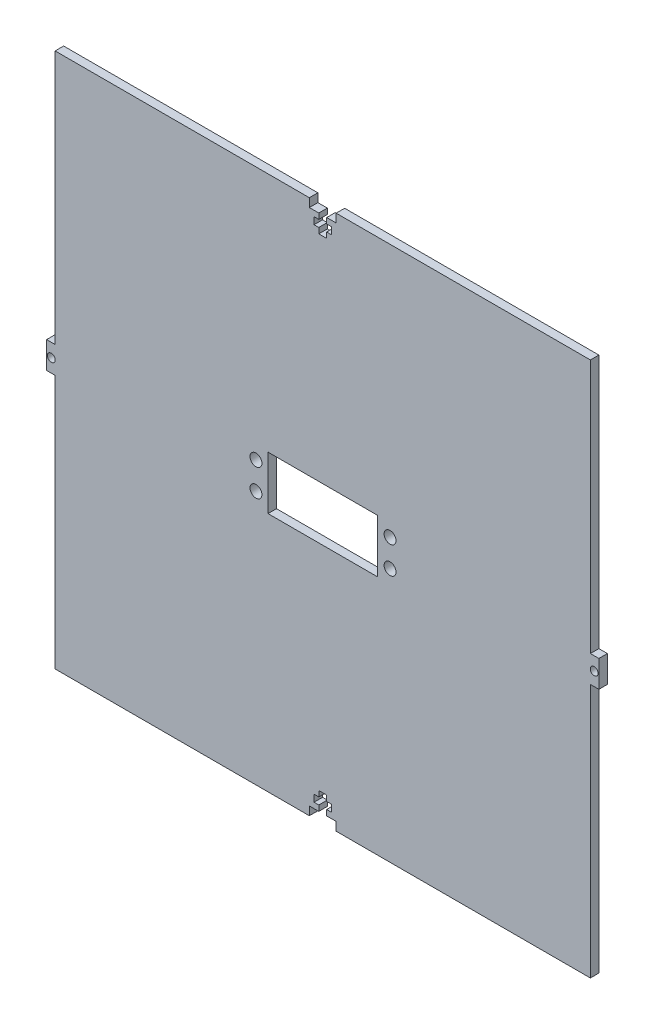
SolidWorks part; units mm, degrees
ref_plane "Front Plane" through (0, 0, 0) normal (0, 0, 1) x (1, 0, 0)
ref_plane "Top Plane" through (0, 0, 0) normal (0, 1, 0) x (1, 0, 0)
ref_plane "Right Plane" through (0, 0, 0) normal (1, 0, 0) x (0, 0, -1)
sketch "Sketch2" plane through (0, 0, 0) normal (0, 0, 1) x (1, 0, 0)
  line L1 (-100, -100) -> (100, -100)
  line L2 (-100, -100) -> (-100, 100)
  line L3 (-100, 100) -> (100, 100)
  line L4 (100, -100) -> (100, 100)
  line L5 (-100, -100) -> (100, 100) construction
  line L6 (-100, 100) -> (100, -100) construction
  point P0 (0, 0)
  dimension "D1" = 200
  dimension "D2" = 200
extrude "Boss-Extrude1" add sketch "Sketch2" along normal blind 3.18
sketch "Sketch3" plane through (0, 0, 3.18) normal (0, 0, 1) x (1, 0, 0)
  line L0 (100, 100) -> (-100, 100) construction
  line L1 (-5, 100) -> (5, 100)
  line L2 (-5, 100) -> (-5, 96.82)
  line L3 (-5, 96.82) -> (-1.47, 96.82)
  line L4 (5, 100) -> (5, 96.82)
  line L5 (0, 100) -> (0, 25.4128) construction
  line L6 (1.47, 92.14) -> (3.25, 92.14)
  line L8 (-1.47, 96.82) -> (-1.47, 94.74)
  line L9 (-1.47, 90.07) -> (1.47, 90.07)
  line L10 (1.47, 96.82) -> (1.47, 94.74)
  line L11 (-3.25, 94.74) -> (-1.47, 94.74)
  line L12 (-3.25, 94.74) -> (-3.25, 92.14)
  line L13 (-3.25, 92.14) -> (-1.47, 92.14)
  line L14 (3.25, 94.74) -> (3.25, 92.14)
  line L15 (-1.47, 92.14) -> (-1.47, 90.07)
  line L16 (1.47, 94.74) -> (3.25, 94.74)
  line L17 (1.47, 96.82) -> (5, 96.82)
  line L18 (1.47, 92.14) -> (1.47, 90.07)
  line L19 (-100, 0) -> (100, 0) construction
  line L20 (-100, 100) -> (-100, -100) construction
  line L21 (100, -100) -> (100, 100) construction
  line L22 (1.47, -96.82) -> (5, -96.82)
  line L23 (5, -100) -> (5, -96.82)
  line L24 (-5, -100) -> (5, -100)
  line L25 (-5, -100) -> (-5, -96.82)
  line L26 (-5, -96.82) -> (-1.47, -96.82)
  line L27 (-1.47, -96.82) -> (-1.47, -94.74)
  line L28 (-3.25, -94.74) -> (-1.47, -94.74)
  line L29 (-3.25, -94.74) -> (-3.25, -92.14)
  line L30 (-3.25, -92.14) -> (-1.47, -92.14)
  line L31 (-1.47, -92.14) -> (-1.47, -90.07)
  line L32 (-1.47, -90.07) -> (1.47, -90.07)
  line L33 (1.47, -92.14) -> (1.47, -90.07)
  line L34 (1.47, -92.14) -> (3.25, -92.14)
  line L35 (3.25, -94.74) -> (3.25, -92.14)
  line L36 (1.47, -94.74) -> (3.25, -94.74)
  line L37 (1.47, -96.82) -> (1.47, -94.74)
  dimension "D1" = 3.18
  dimension "D2" = 10
  dimension "D3" = 2.94
  dimension "D4" = 2.6
  dimension "D5" = 6.75
  dimension "D6" = 6.5
  dimension "D7" = 2.08
extrude "Cut-Extrude1" cut sketch "Sketch3" against normal through all
sketch "Sketch4" plane through (-100, 0, 0) normal (-1, 0, 0) x (0, 0, 1)
  line L0 (0, 100) -> (0, -100) construction
  line L1 (0, -5) -> (3.18, -5)
  line L2 (0, -5) -> (0, 5)
  line L3 (0, 5) -> (3.18, 5)
  line L4 (3.18, -5) -> (3.18, 5)
  line L5 (3.18, 100) -> (3.18, -100) construction
  line L6 (0, 0) -> (19.9881, 0) construction
  dimension "D1" = 10
extrude "Boss-Extrude2" add sketch "Sketch4" along normal blind 3.18
sketch "Sketch6" plane through (0, 0, 3.18) normal (0, 0, 1) x (1, 0, 0)
  line L0 (-103.18, 0) -> (0, 0) construction
  line L1 (-103.18, -5) -> (-103.18, 5) construction
  circle A1 centre (-101.43, 0) radius 1.47
  dimension "D1" = 2.94
  dimension "D2" = 1.75
extrude "Cut-Extrude2" cut sketch "Sketch6" against normal through all
mirror "Mirror1" about plane through (0, 0, 0) normal (1, 0, 0) of "Boss-Extrude2"
mirror "Mirror2" about plane through (0, 0, 0) normal (1, 0, 0) of "Cut-Extrude2"
sketch "Sketch8" plane through (0, 0, 3.18) normal (0, 0, 1) x (1, 0, 0)
  line L1 (-20.45, -9.95) -> (20.45, -9.95)
  line L2 (-20.45, -9.95) -> (-20.45, 9.95)
  line L3 (-20.45, 9.95) -> (20.45, 9.95)
  line L4 (20.45, -9.95) -> (20.45, 9.95)
  line L5 (-20.45, -9.95) -> (20.45, 9.95) construction
  line L6 (-20.45, 9.95) -> (20.45, -9.95) construction
  point P0 (0, 0)
  dimension "D1" = 19.9
  dimension "D2" = 40.9
extrude "Cut-Extrude4" cut sketch "Sketch8" against normal through all
sketch "Sketch10" plane through (0, 0, 3.18) normal (0, 0, 1) x (1, 0, 0)
  circle A0 centre (-24.949, 5.1875) radius 2.2225
  circle A1 centre (-24.949, -4.9725) radius 2.2225
  circle A2 centre (25.149, 5.1875) radius 2.2225
  circle A3 centre (25.149, -4.9725) radius 2.2225
extrude "Cut-Extrude6" cut sketch "Sketch10" against normal through all
